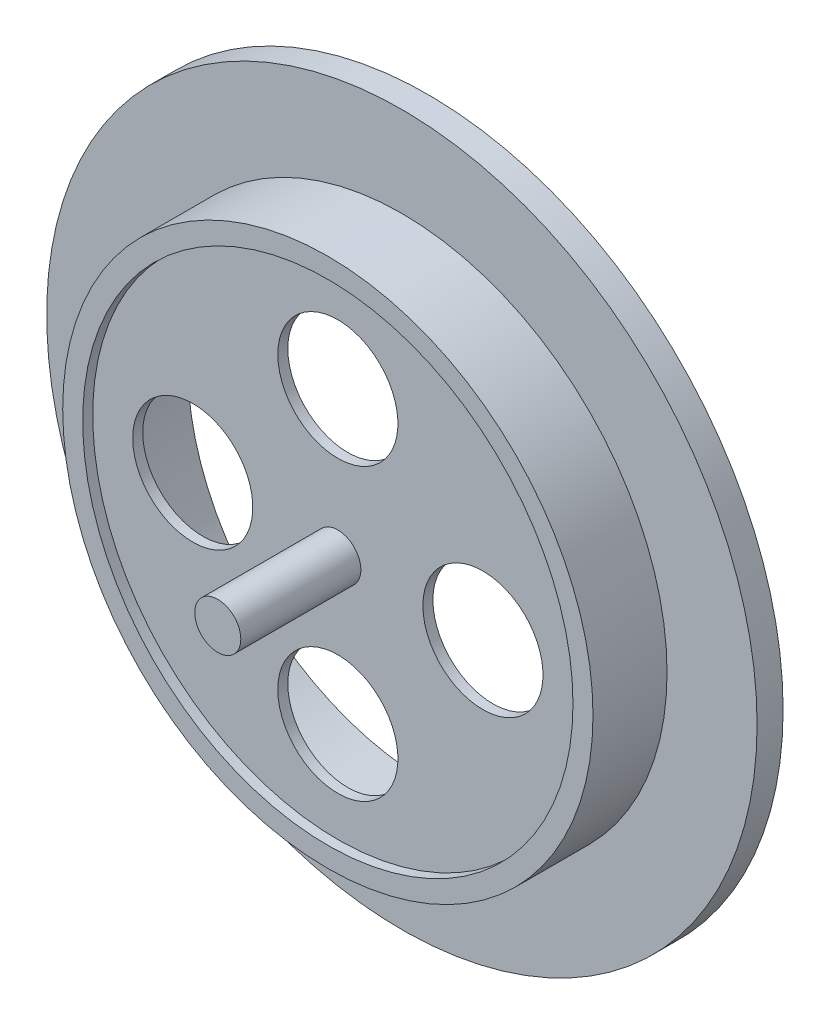
SolidWorks part; units mm, degrees
ref_plane "Front Plane" through (0, 0, 0) normal (0, 0, 1) x (1, 0, 0)
ref_plane "Top Plane" through (0, 0, 0) normal (0, 1, 0) x (1, 0, 0)
ref_plane "Right Plane" through (0, 0, 0) normal (1, 0, 0) x (0, 0, -1)
sketch "Sketch1" plane through (0, 0, 0) normal (0, 0, 1) x (1, 0, 0)
  circle A0 centre (0, 0) radius 17.75
  dimension "D1" = 35.5
extrude "Boss-Extrude1" add sketch "Sketch1" along normal blind 1.3
sketch "Sketch2" plane through (0, 0, 1.3) normal (0, 0, 1) x (1, 0, 0)
  circle A0 centre (0, 0) radius 13.25
  dimension "D1" = 26.5
extrude "Boss-Extrude2" add sketch "Sketch2" along normal blind 3.7
sketch "Sketch3" plane through (0, 0, 0) normal (0, 0, -1) x (-1, 0, 0)
  circle A0 centre (0, 0) radius 12
  dimension "D1" = 24
extrude "Cut-Extrude1" cut sketch "Sketch3" against normal blind 4
sketch "Sketch4" plane through (0, 0, 5) normal (0, 0, 1) x (1, 0, 0)
  circle A0 centre (0, 0) radius 12.25
  dimension "D1" = 24.5
extrude "Cut-Extrude2" cut sketch "Sketch4" against normal blind 0.5
sketch "Sketch5" plane through (0, 0, 4) normal (0, 0, -1) x (-1, 0, 0)
  circle A0 centre (0, 7.25) radius 3
  circle A1 centre (7.25, 0) radius 3
  circle A2 centre (0, -7.25) radius 3
  circle A3 centre (-7.25, 0) radius 3
  point P12 (0, 0)
  dimension "D1" = 6
  dimension "D2" = 7.25
  dimension "D3" = 4
extrude "Cut-Extrude3" cut sketch "Sketch5" against normal blind 0.5
sketch "Sketch6" plane through (0, 0, 4.5) normal (0, 0, 1) x (1, 0, 0)
  circle A0 centre (0, 0) radius 1.15
  dimension "D1" = 2.3
extrude "Boss-Extrude3" add sketch "Sketch6" along normal blind 6
